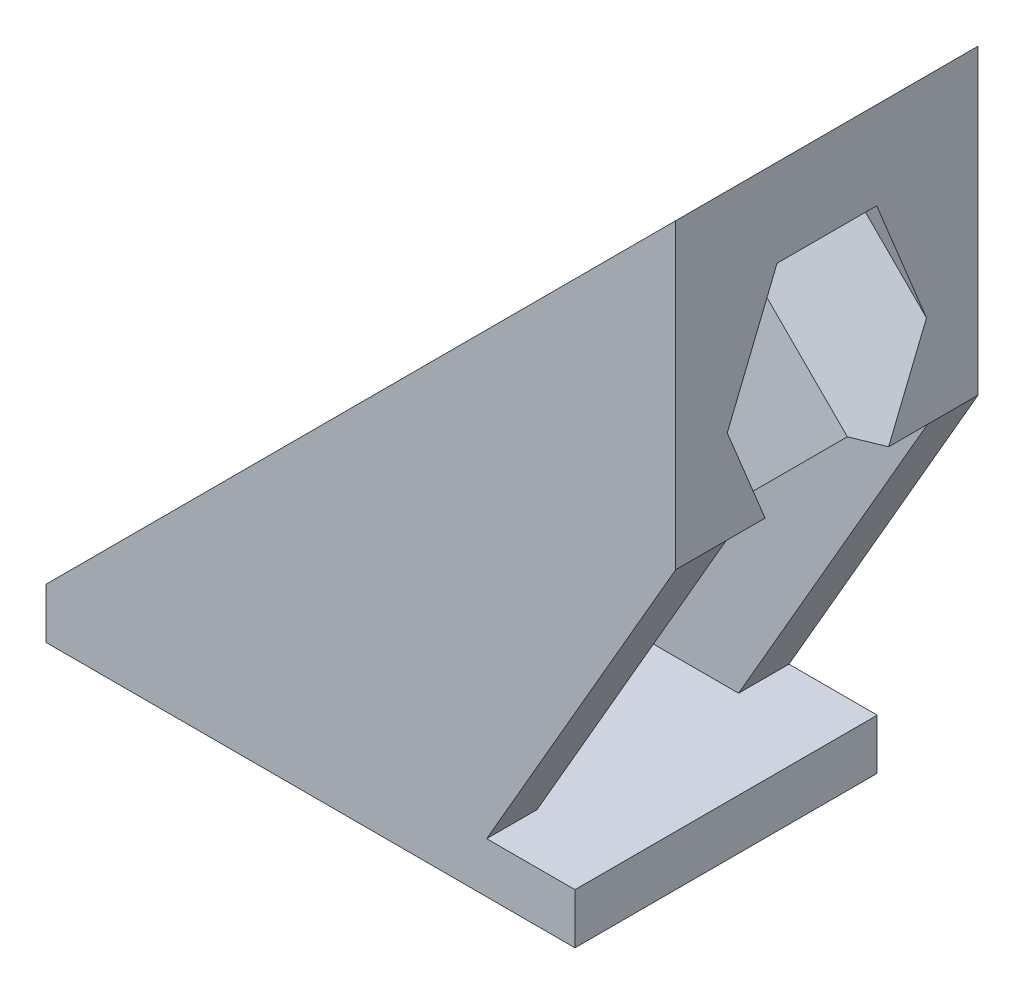
SolidWorks part; units mm, degrees
ref_plane "Front Plane" through (0, 0, 0) normal (0, 0, 1) x (1, 0, 0)
ref_plane "Top Plane" through (0, 0, 0) normal (0, 1, 0) x (1, 0, 0)
ref_plane "Right Plane" through (0, 0, 0) normal (1, 0, 0) x (0, 0, -1)
sketch "Sketch3" plane through (0, 0, 0) normal (0, 0, 1) x (1, 0, 0)
  line L0 (0, 0) -> (21, 0)
  line L1 (0, 0) -> (25, 25)
  line L2 (25, 25) -> (25, 13)
  line L3 (25, 13) -> (17.4944, 0)
  line L4 (25, 13) -> (13, 13)
  line L5 (0, 0) -> (0, -2)
  line L6 (0, -2) -> (21, -2)
  line L7 (21, -2) -> (21, 0)
  dimension "D1" = 21
  dimension "D2" = 45
  dimension "D3" = 25
  dimension "D4" = 12
  dimension "D5" = 60
  dimension "D6" = 2
extrude "Boss-Extrude1" add sketch "Sketch3" along normal blind 12 contours L6 L7 L0 L5 | L3 L4 L1 L0 | L4 L2 L1
sketch "Sketch4" plane through (0, 0, 12) normal (0, 0, 1) x (1, 0, 0)
  line L0 (25, 13) -> (20, 13)
  line L1 (20, 13) -> (3, 0)
  line L2 (3, 0) -> (17.4944, 0)
  line L3 (17.4944, 0) -> (25, 13)
  dimension "D1" = 5
extrude "Cut-Extrude1" cut sketch "Sketch4" against normal blind 8 from offset 2 offset against normal yes
sketch "Sketch7" plane through (0, 0, 0) normal (-0.7071, 0.7071, 0) x (0, 0, 1)
  line L0 (0, 35.3553) -> (0, 23.3553)
  line L1 (0, 0) -> (0, 35.3553) construction
  line L2 (0, 23.3553) -> (12, 23.3553)
  line L3 (12, 0) -> (12, 35.3553) construction
  line L4 (12, 23.3553) -> (12, 35.3553)
  line L5 (12, 35.3553) -> (0, 35.3553)
  line L6 (6, 35.3553) -> (6, 23.3553)
  line L8 (9.9548, 29.4726) -> (7.9774, 32.8976)
  line L9 (7.9774, 32.8976) -> (4.0226, 32.8976)
  line L10 (4.0226, 32.8976) -> (2.0452, 29.4726)
  line L11 (2.0452, 29.4726) -> (4.0226, 26.0476)
  line L12 (4.0226, 26.0476) -> (7.9774, 26.0476)
  line L13 (7.9774, 26.0476) -> (9.9548, 29.4726)
  circle A0 centre (6, 29.4726) radius 3.425 construction
  dimension "D1" = 12
extrude "Cut-Extrude8" cut sketch "Sketch7" against normal through all from offset 2 contours L11 L12 L6 L9 L10 | L12 L13 L8 L9 L6 offset against normal yes
sketch "Sketch8" plane through (0, 0, 0) normal (-0.7071, 0.7071, 0) x (0, 0, 1)
  line L0 (0, 35.3553) -> (0, 23.3553)
  line L1 (0, 0) -> (0, 35.3553) construction
  line L2 (6, 35.3553) -> (6, 23.3553)
  line L3 (12, 35.3553) -> (0, 35.3553) construction
  circle A0 centre (6, 29.3553) radius 2
  dimension "D1" = 12
extrude "Cut-Extrude9" cut sketch "Sketch8" against normal through all contours L2 A0 | L2 A0
sketch "Sketch9" plane through (0, 0, 0) normal (0, 1, 0) x (1, 0, 0)
  line L0 (3, -10) -> (17.4944, -2)
  line L1 (17.4944, -2) -> (16.395, -3.0709)
  circle A1 centre (10.2472, -6) radius 2
  circle A2 centre (10.2472, -6) radius 5
  point P8 (10.2472, -6)
  line M3 (17.4944, -2) -> (3, -2)
  line M5 (3, -10) -> (17.4944, -10)
  dimension "D1" = 10
extrude "Cut-Extrude11" cut sketch "Sketch9" along normal blind 2 contours L0 A2 A1 M3 | A2 L0 A1 M5 | L0 A1 | L0 A1 | A2 M3 | A2 M5
sketch "Sketch12" plane through (0, 0, 0) normal (0, 1, 0) x (1, 0, 0)
  line L0 (3, -10) -> (17.4944, -10)
  line L1 (17.4944, -10) -> (17.4944, -2)
  line L2 (17.4944, -2) -> (3, -2)
  line L3 (3, -2) -> (3, -10)
  line L4 (3, -6) -> (17.4944, -6)
  circle A0 centre (10.2472, -6) radius 2
  point P10 (10.2472, -6)
hole_wizard "CSK for M4 Flat Head Machine Screw1" positions "Sketch12" profile "Sketch13" countersink size "M4" standard "ANSI Metric" end condition through all
sketch "Sketch13" plane through (10.2472, 0, 6) normal (1, 0, 0) x (0, 0, 1)
  line L0 (0, 0) -> (0, 2)
  line L1 (0, 2) -> (2.15, 2)
  line L2 (2.15, 2) -> (2.15, 2.55)
  line L3 (2.15, 2.55) -> (4.7, 0)
  line L5 (4.7, 0) -> (0, 0)
  line L6 (-2.15, 2.55) -> (-4.7, 0) construction
  line L11 (0, -6.35) -> (0, 107.95) construction
  dimension "Thru Hole Dia." = 4.3
  dimension "Thru Hole Depth" = 2
  dimension "Near C'Sink Dia." = 9.4
  dimension "Near C'Sink Angle" = 90
fillet "Fillet1" radius 10 1 edges at (20, 13, 6)
